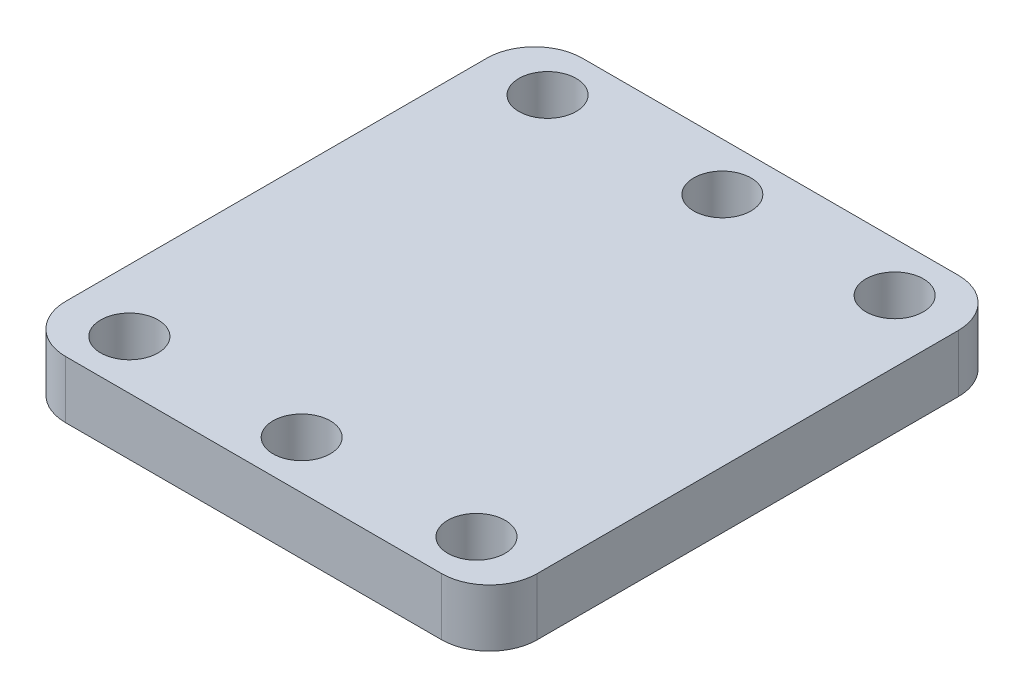
SolidWorks part; units mm, degrees
ref_plane "Alzado" through (0, 0, 0) normal (0, 0, 1) x (1, 0, 0)
ref_plane "Planta" through (0, 0, 0) normal (0, 1, 0) x (1, 0, 0)
ref_plane "Vista lateral" through (0, 0, 0) normal (1, 0, 0) x (0, 0, -1)
sketch "Croquis1" plane through (0, 0, 0) normal (0, 1, 0) x (1, 0, 0)
  line L0 (0.0546, -4.5342) -> (4.5262, -4.5342) construction
  line L1 (-4.7151, 6.4658) -> (10.2849, 6.4658) construction
  line L2 (-4.7151, 6.4658) -> (-4.7151, -15.5342) construction
  line L3 (-4.7151, -15.5342) -> (10.2849, -15.5342) construction
  line L6 (10.2849, 6.4658) -> (10.2849, -15.5342) construction
  line L12 (-4.7151, 6.4658) -> (10.2849, -15.5342) construction
  line L13 (-4.7151, -15.5342) -> (10.2849, 6.4658) construction
  line L14 (-7.0443, 8.9765) -> (12.614, 8.9765)
  line L15 (-9.5443, 6.4765) -> (-9.5443, -15.5448)
  line L16 (-7.0443, -18.0448) -> (12.614, -18.0448)
  line L17 (15.114, 6.4765) -> (15.114, -15.5448)
  line L18 (-9.5443, 8.9765) -> (15.114, -18.0448) construction
  line L19 (-9.5443, -18.0448) -> (15.114, 8.9765) construction
  circle A10 centre (2.7849, 6.4658) radius 1.4982
  circle A11 centre (2.7849, -15.5342) radius 1.4982
  circle A12 centre (-6.2903, 6.4004) radius 1.5
  circle A13 centre (-6.2903, -15.4687) radius 1.5
  circle A14 centre (11.86, -15.4687) radius 1.5
  circle A15 centre (11.86, 6.4004) radius 1.5
  arc A16 (-7.0443, -18.0448) -> (-9.5443, -15.5448) centre (-7.0443, -15.5448) cw
  arc A17 (12.614, -18.0448) -> (15.114, -15.5448) centre (12.614, -15.5448) ccw
  arc A18 (12.614, 8.9765) -> (15.114, 6.4765) centre (12.614, 6.4765) cw
  arc A19 (-7.0443, 8.9765) -> (-9.5443, 6.4765) centre (-7.0443, 6.4765) ccw
  point P0 (2.7849, -4.5342)
  point P19 (2.7849, -4.5342)
  point P39 (0, 0)
extrude "Saliente-Extruir1" add sketch "Croquis1" along normal mid plane 3
